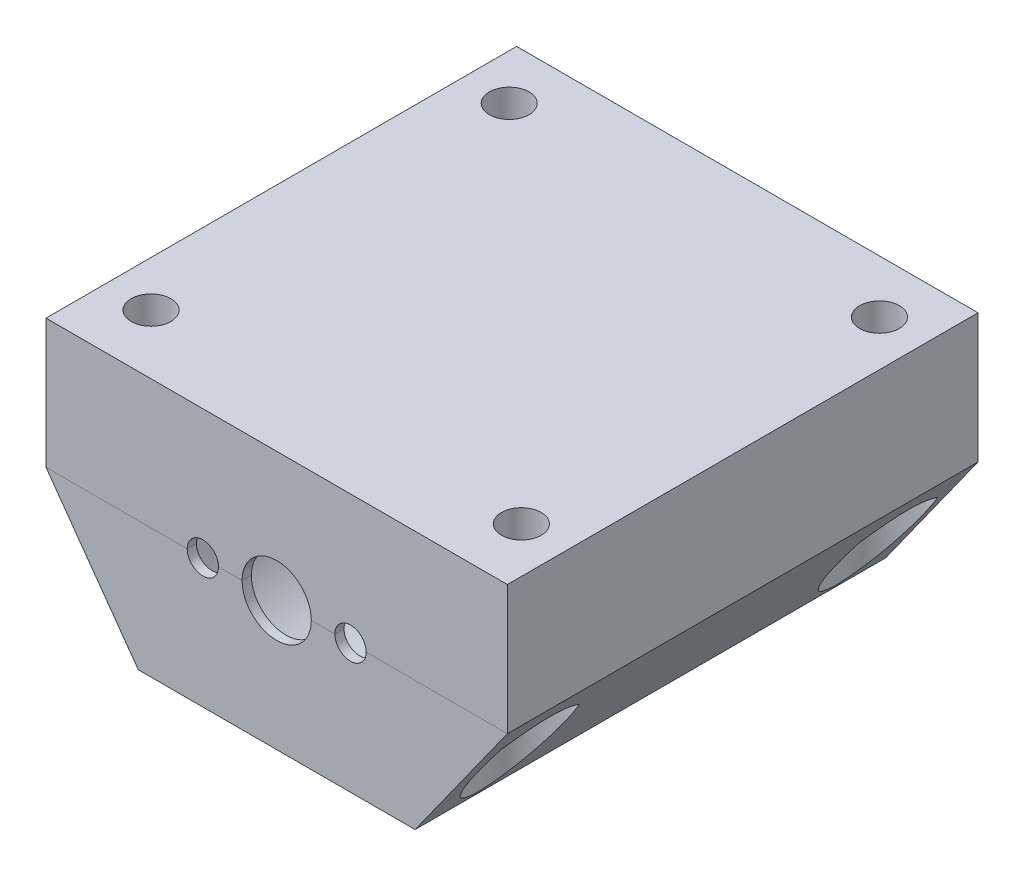
SolidWorks part; units mm, degrees
ref_plane "Plan de face" through (0, 0, 0) normal (0, 0, 1) x (1, 0, 0)
ref_plane "Plan de dessus" through (0, 0, 0) normal (0, 1, 0) x (1, 0, 0)
ref_plane "Plan de droite" through (0, 0, 0) normal (1, 0, 0) x (0, 0, -1)
sketch "Esquisse1" plane through (0, 0, 0) normal (0, 0, 1) x (1, 0, 0)
  line L4 (0, 12.5) -> (0, 14) construction
  line L5 (0, -12.5) -> (0, -14) construction
  line L7 (-15, 14) -> (15, 14)
  line L8 (15, 14) -> (15, -14)
  line L9 (15, -14) -> (-15, -14)
  line L10 (-15, -14) -> (-15, 14)
  line L11 (-15, 0) -> (-25, 0)
  line L12 (-25, 0) -> (-25, 14)
  line L13 (-25, 14) -> (-15, 14)
  line L14 (15, 14) -> (25, 14)
  line L15 (25, 14) -> (25, 0)
  line L16 (25, 0) -> (15, 0)
  line L17 (-25, 0) -> (-15, -14)
  line L18 (15, -14) -> (25, 0)
  line L19 (25, 0) -> (-25, 0) construction
  circle A0 centre (0, 0) radius 12.5
  point P9 (0, 14)
  dimension "D1" = 25
  dimension "D2" = 30
  dimension "D3" = 1.5
  dimension "D4" = 1.5
  dimension "D5" = 10
  dimension "D6" = 10
extrude "Boss.-Extru.1" add sketch "Esquisse1" along normal blind 50 contours L13 L12 L11 L10 | L11 L17 L10 | L10 L9 L8 L7 A0 | L8 L18 L16 | L16 L15 L14 L8
ref_plane "Plan1" through (0, 0, 0) normal (0, 1, 0) x (1, 0, 0)
hole_wizard "Fraisage pour vis à tête fraisée M41" positions "Esquisse24" profile "Esquisse25" countersink size "M4" standard "ISO" end condition through all
sketch "Esquisse24" plane through (0, -14, 0) normal (0, -1, 0) x (-1, 0, 0)
  point P0 (-20.0635, -5.7391)
  point P2 (20.0635, -5.7391)
  point P4 (20.0635, -44.5528)
  point P6 (-20.0635, -44.5528)
sketch "Esquisse25" plane through (20.0635, -14, 5.7391) normal (1, 0, 0) x (0, 0, -1)
  line L0 (0, 0) -> (0, 28)
  line L1 (0, 28) -> (2.15, 28)
  line L2 (2.15, 28) -> (2.15, 12.55)
  line L3 (2.15, 12.55) -> (4.7, 10)
  line L4 (4.7, 10) -> (4.7, 0)
  line L6 (4.7, 0) -> (0, 0)
  line L7 (-2.15, 12.55) -> (-4.7, 10) construction
  line L11 (0, -6.35) -> (0, 107.95) construction
  dimension "Diamètre du perçage jusqu'au prochain" = 4.3
  dimension "Profondeur du perçage jusqu'au prochain" = 28
  dimension "Diamètre du fraisage" = 9.4
  dimension "Angle du fraisage" = 90
  dimension "Dégagement de la tête" = 10
sketch "Esquisse26" plane through (0, 0, 50) normal (0, 0, 1) x (1, 0, 0)
  line L0 (-25, 14) -> (-25, 0)
  line L1 (27.5, 0) -> (-27.5, 0) construction
  line L2 (-25, 0) -> (-15, -14) construction
  line L3 (-25, 0) -> (-15, -14)
  line L4 (-15, -14) -> (15, -14)
  line L5 (15, -14) -> (25, 0)
  line L6 (15, -14) -> (25, 0) construction
  line L7 (25, 0) -> (25, 14)
  line L8 (25, 14) -> (25, 0) construction
  line L9 (-25, 14) -> (25, 14) construction
  line L10 (25, 14) -> (-25, 14)
  circle A0 centre (0, 0) radius 3.75
  dimension "D1" = 7.5
extrude "Boss.-Extru.2" add sketch "Esquisse26" along normal blind 1
hole_wizard "Dégagement M31" positions "Esquisse27" profile "Esquisse28" hole size "M3" standard "ISO" end condition through all
sketch "Esquisse27" plane through (0, 0, 51) normal (0, 0, 1) x (1, 0, 0)
  line L0 (27.5, 0) -> (-27.5, 0) construction
  point P0 (-8, 0)
  point P4 (8, 0)
  dimension "D1" = 8
  dimension "D2" = 16
sketch "Esquisse28" plane through (-8, 0, 51) normal (1, 0, 0) x (0, -1, 0)
  line L0 (0, 0) -> (0, 51)
  line L1 (0, 51) -> (1.7, 51)
  line L2 (1.7, 51) -> (1.7, 0)
  line L5 (1.7, 0) -> (0, 0)
  line L11 (0, -6.35) -> (0, 107.95) construction
  dimension "Diamètre du perçage jusqu'au prochain" = 3.4
  dimension "Profondeur du perçage jusqu'au prochain" = 51
split "Fractionner1" trim tools "Plan1" bodies to split 118 resulting bodies 119 120
